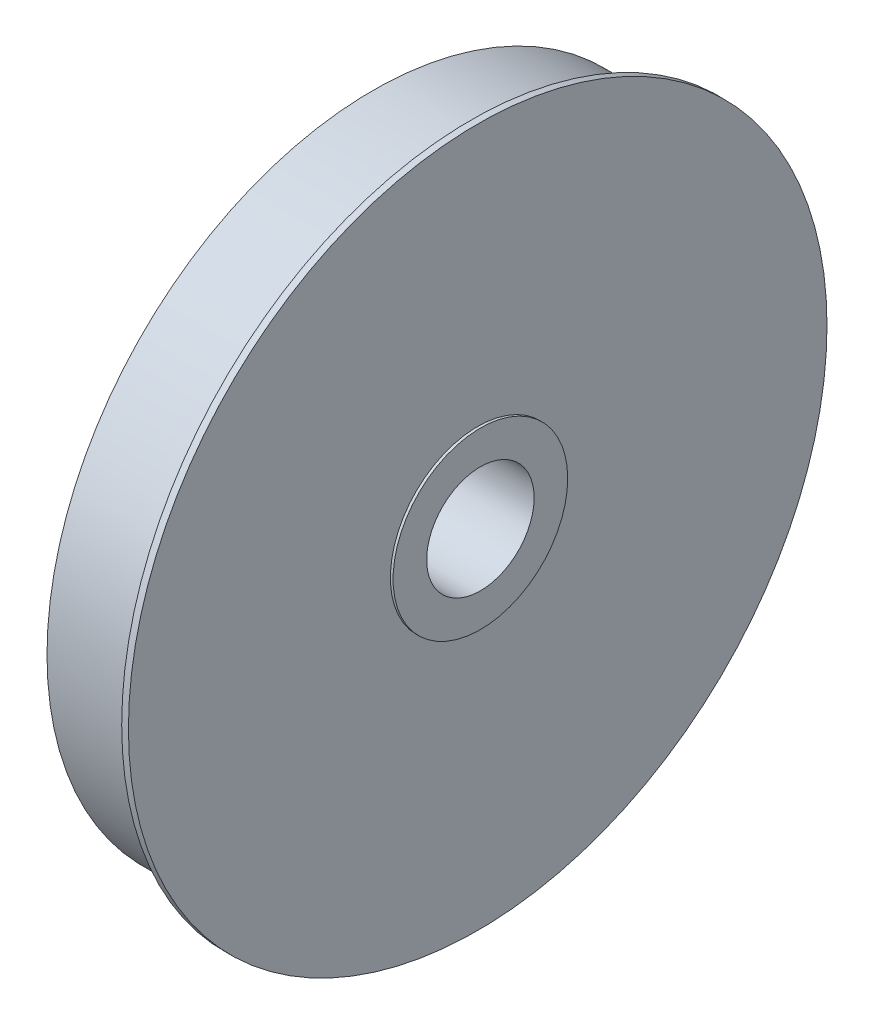
SolidWorks part; units mm, degrees
ref_plane "Plan1" through (0, 0, 0) normal (0, 0, 1) x (1, 0, 0)
ref_plane "Plan2" through (0, 0, 0) normal (0, 1, 0) x (1, 0, 0)
ref_plane "Plan3" through (0, 0, 0) normal (1, 0, 0) x (0, 0, -1)
sketch "Esquisse1" plane through (0, 0, 0) normal (0, 0, 1) x (1, 0, 0)
  line L0 (0, 0) -> (8.8, 0)
  line L1 (0, 0) -> (0, 20)
  line L2 (8.8, 26) -> (8.3, 26)
  line L3 (8.8, 26) -> (8.8, 0)
  line L4 (7.8, 25.134) -> (8.3, 26)
  line L5 (-7.9562, 0) -> (18.7115, 0) construction
  line L6 (7.8, 24.26) -> (1, 24.26)
  line L7 (7.8, 24.26) -> (7.8, 25.134)
  line L10 (1, 20) -> (0, 20)
  line L11 (1, 20) -> (1, 24.26)
  dimension "D1" = 26
  dimension "D2" = 24.26
  dimension "D3" = 20
  dimension "D4" = 1
  dimension "D5" = 1
  dimension "D6" = 8.8
  dimension "D7" = 0.5
  dimension "D8" = 30
revolve "Base-Révolution" add sketch "Esquisse1" angle 360 about L5
hole_wizard "Perçage1" positions "Esquisse3" profile "Esquisse2" legacy
sketch "Esquisse3" plane through (8.8, 0, 0) normal (1, 0, 0) x (0, 0, -1)
  point P0 (0, 0)
sketch "Esquisse2" plane through (8.8, 0, 0) normal (0, 1, 0) x (0, 0, -1)
  line L0 (0, 0) -> (0, 8.8)
  line L1 (0, 8.8) -> (4, 8.8)
  line L2 (4, 8.8) -> (4, 0)
  line L3 (4, 0) -> (0, 0)
  line L4 (0, 110) -> (0, -10) construction
  dimension "Diamètre" = 8
  dimension "Profondeur" = 8.8
sketch "Esquisse13" plane through (8.8, 0, 0) normal (1, 0, 0) x (0, 0, -1)
  circle A0 centre (0, 0) radius 6.5
  circle A1 centre (0, 0) radius 4
  dimension "D1" = 13
  dimension "D2" = 8
extrude "Boss.-Extru.1" add sketch "Esquisse13" along normal blind 0.2
